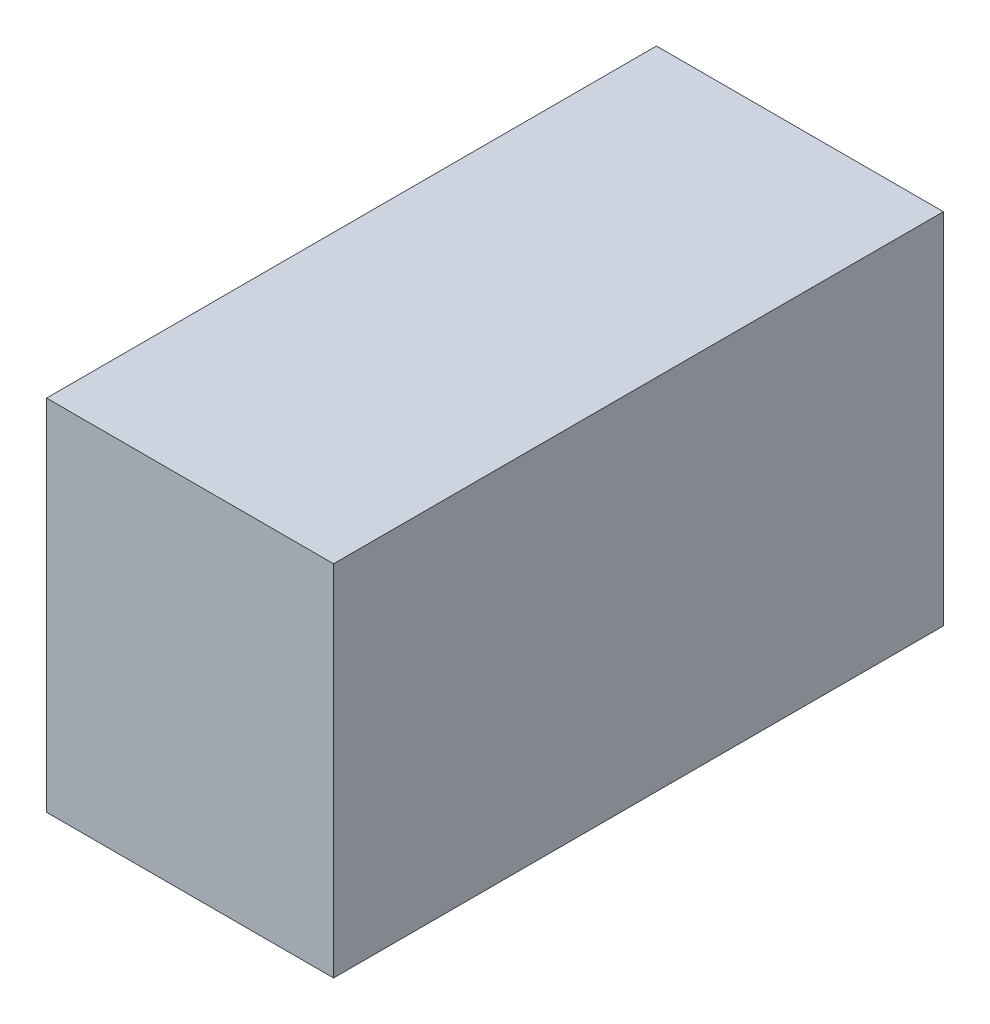
SolidWorks part; units mm, degrees
ref_plane "Front Plane" through (0, 0, 0) normal (0, 0, 1) x (1, 0, 0)
ref_plane "Top Plane" through (0, 0, 0) normal (0, 1, 0) x (1, 0, 0)
ref_plane "Right Plane" through (0, 0, 0) normal (1, 0, 0) x (0, 0, -1)
sketch "Sketch1" plane through (0, 0, 0) normal (0, 0, 1) x (1, 0, 0)
  line L1 (-12.7, 15.875) -> (12.7, 15.875)
  line L2 (-12.7, 15.875) -> (-12.7, -15.875)
  line L3 (-12.7, -15.875) -> (12.7, -15.875)
  line L4 (12.7, 15.875) -> (12.7, -15.875)
  line L5 (-12.7, 15.875) -> (12.7, -15.875) construction
  line L6 (-12.7, -15.875) -> (12.7, 15.875) construction
  point P0 (0, 0)
  dimension "D1" = 25.4
  dimension "D2" = 31.75
extrude "Boss-Extrude1" add sketch "Sketch1" along normal mid plane 53.975
sketch "Sketch2" plane through (0, 0, 0) normal (0, 0, 1) x (1, 0, 0)
  line L0 (12.7, 15.875) -> (-12.7, 15.875) construction
  line L1 (-12.446, -15.621) -> (12.446, -15.621)
  line L2 (-12.446, -15.621) -> (-12.446, 15.621)
  line L3 (-12.446, 15.621) -> (12.446, 15.621)
  line L4 (12.446, -15.621) -> (12.446, 15.621)
  line L5 (-12.446, -15.621) -> (12.446, 15.621) construction
  line L6 (-12.446, 15.621) -> (12.446, -15.621) construction
  line L7 (12.7, -15.875) -> (12.7, 15.875) construction
  point P0 (0, 0)
  dimension "D1" = 0.254
  dimension "D2" = 0.254
extrude "Boss-Extrude2" add sketch "Sketch2" along normal mid plane 53.467 separate body
sketch "Sketch3" plane through (12.446, 0, 0) normal (1, 0, 0) x (0, 0, -1)
  line L0 (-26.7335, 11.7223) -> (-20.3835, 14.0335)
  line L1 (-26.7335, -15.621) -> (-26.7335, 15.621) construction
  line L2 (-20.3835, 14.0335) -> (-20.3835, 15.621)
  line L3 (-26.7335, 15.621) -> (26.7335, 15.621) construction
  line L4 (-20.3835, 15.621) -> (-26.7335, 15.621)
  line L5 (-26.7335, 15.621) -> (-26.7335, 11.7223)
  line L6 (-20.3835, 14.0335) -> (-26.7335, 14.0335) construction
  line L7 (-25.7351, 12.0857) -> (-26.7335, 11.0873) construction
  line L8 (-26.7335, 11.0873) -> (-26.7335, 11.7223) construction
  line L9 (-26.7335, 11.7223) -> (-25.7351, 12.0857) construction
  line L10 (-26.7335, 11.7223) -> (-26.7335, 11.0873) construction
  dimension "D1" = 1.5875
  dimension "D3" = 20
  dimension "D4" = 45
  dimension "D5" = 0.635
extrude "Cut-Extrude1" cut sketch "Sketch3" against normal through all
mirror "Mirror1" about plane through (0, 0, 0) normal (0, 1, 0) of "Cut-Extrude1"
mirror "Mirror2" about plane through (0, 0, 0) normal (0, 0, 1) of "Mirror1", "Cut-Extrude1"
sketch "Sketch4" plane through (0, 15.621, 0) normal (0, 1, 0) x (1, 0, 0)
  line L0 (-12.446, 26.7335) -> (-12.446, 20.3835)
  line L2 (-12.446, -20.3835) -> (-12.446, 20.3835) construction
  line L3 (-12.446, 20.3835) -> (-10.8585, 20.3835)
  line L5 (-10.8585, 20.3835) -> (-8.5473, 26.7335)
  line L8 (-8.5473, 26.7335) -> (-12.446, 26.7335)
  line L9 (-10.8585, 20.3835) -> (-10.8585, 26.7335) construction
  dimension "D3" = 6.35
  dimension "D4" = 1.5875
  dimension "D5" = 20
extrude "Cut-Extrude2" cut sketch "Sketch4" against normal through all and the other way through all
mirror "Mirror3" about plane through (0, 0, 0) normal (1, 0, 0) of "Cut-Extrude2"
mirror "Mirror4" about plane through (0, 0, 0) normal (0, 0, 1) of "Mirror3", "Cut-Extrude2"
chamfer "Chamfer1" [suppressed] distance 2.54 angle 45
sketch "Sketch5" plane through (0, 0, 0) normal (1, 0, 0) x (0, 0, -1)
  line L0 (12.6662, 224.3643) -> (176.6662, 224.3643) construction
sketch "Sketch6" plane through (0, -15.621, 0) normal (0, -1, 0) x (1, 0, 0)
  circle A0 centre (0, 0) radius 9.906 construction
  circle A1 centre (0, 0) radius 9.906 construction
  circle A2 centre (0, 0) radius 5.7544
  dimension "D1" = 11.5087
extrude "Cut-Extrude3" cut sketch "Sketch6" against normal up to surface (12.446 mm away)
sketch "Sketch7" plane through (0, -15.621, 0) normal (0, -1, 0) x (1, 0, 0)
  circle A0 centre (0, 0) radius 9.906 construction
  circle A1 centre (0, 0) radius 9.906 construction
  circle A2 centre (0, 0) radius 7.3419
  dimension "D1" = 14.6837
extrude "Cut-Extrude5" cut sketch "Sketch7" against normal up to surface (6.096 mm away)
sketch "rightGraphics" plane through (12.446, 0, 0) normal (1, 0, 0) x (0, 0, -1)
  line L2 (26.7335, 11.7223) -> (26.7335, -11.7223)
  line L4 (-26.7335, -11.7223) -> (-26.7335, 11.7223)
  line L10 (26.7335, -11.7223) -> (20.3835, -14.0335)
  line L11 (26.7335, -11.7223) -> (20.3835, -14.0335)
  line L12 (20.3835, -14.0335) -> (20.3835, -15.621)
  line L14 (20.3835, -15.621) -> (-20.3835, -15.621)
  line L16 (-20.3835, -15.621) -> (-20.3835, -14.0335)
  line L18 (-20.3835, -14.0335) -> (-26.7335, -11.7223)
  line L19 (-20.3835, -14.0335) -> (-26.7335, -11.7223)
  line L30 (-26.7335, 11.7223) -> (-20.3835, 14.0335)
  line L31 (-26.7335, 11.7223) -> (-20.3835, 14.0335)
  line L32 (-20.3835, 14.0335) -> (-20.3835, 15.621)
  line L34 (-20.3835, 15.621) -> (20.3835, 15.621)
  line L36 (20.3835, 15.621) -> (20.3835, 14.0335)
  line L38 (20.3835, 14.0335) -> (26.7335, 11.7223)
  line L39 (20.3835, 14.0335) -> (26.7335, 11.7223)
  line L41 (26.7335, 11.7223) -> (26.7335, -11.7223)
  line L46 (20.3835, -14.0335) -> (20.3835, -15.621)
  line L47 (20.3835, -15.621) -> (-20.3835, -15.621)
  line L48 (-20.3835, -15.621) -> (-20.3835, -14.0335)
  line L52 (-26.7335, -11.7223) -> (-26.7335, 11.7223)
  line L56 (-20.3835, 14.0335) -> (-20.3835, 15.621)
  line L57 (-20.3835, 15.621) -> (20.3835, 15.621)
  line L58 (20.3835, 15.621) -> (20.3835, 14.0335)
sketch "topGraphics" plane through (0, 15.621, 0) normal (0, 1, 0) x (1, 0, 0)
  line L0 (-8.5473, 26.7335) -> (8.5473, 26.7335)
  line L2 (-8.5473, 26.7335) -> (8.5473, 26.7335)
  line L4 (8.5473, -26.7335) -> (-8.5473, -26.7335)
  line L10 (8.5473, 26.7335) -> (10.8585, 20.3835)
  line L11 (8.5473, 26.7335) -> (10.8585, 20.3835)
  line L12 (10.8585, 20.3835) -> (12.446, 20.3835)
  line L14 (12.446, 20.3835) -> (12.446, -20.3835)
  line L16 (12.446, -20.3835) -> (10.8585, -20.3835)
  line L18 (10.8585, -20.3835) -> (8.5473, -26.7335)
  line L19 (10.8585, -20.3835) -> (8.5473, -26.7335)
  line L30 (-8.5473, -26.7335) -> (-10.8585, -20.3835)
  line L31 (-8.5473, -26.7335) -> (-10.8585, -20.3835)
  line L32 (-10.8585, -20.3835) -> (-12.446, -20.3835)
  line L34 (-12.446, -20.3835) -> (-12.446, 20.3835)
  line L36 (-12.446, 20.3835) -> (-10.8585, 20.3835)
  line L38 (-10.8585, 20.3835) -> (-8.5473, 26.7335)
  line L39 (-10.8585, 20.3835) -> (-8.5473, 26.7335)
  line L42 (8.5473, -26.7335) -> (-8.5473, -26.7335)
  line L46 (10.8585, 20.3835) -> (12.446, 20.3835)
  line L47 (12.446, 20.3835) -> (12.446, -20.3835)
  line L48 (12.446, -20.3835) -> (10.8585, -20.3835)
  line L56 (-10.8585, -20.3835) -> (-12.446, -20.3835)
  line L57 (-12.446, -20.3835) -> (-12.446, 20.3835)
  line L58 (-12.446, 20.3835) -> (-10.8585, 20.3835)
sketch "bottomGraphics" plane through (0, -15.621, 0) normal (0, -1, 0) x (1, 0, 0)
  line L0 (-8.5473, 26.7335) -> (8.5473, 26.7335)
  line L2 (-8.5473, 26.7335) -> (8.5473, 26.7335)
  line L4 (8.5473, -26.7335) -> (-8.5473, -26.7335)
  line L10 (8.5473, 26.7335) -> (10.8585, 20.3835)
  line L11 (8.5473, 26.7335) -> (10.8585, 20.3835)
  line L12 (10.8585, 20.3835) -> (12.446, 20.3835)
  line L14 (12.446, 20.3835) -> (12.446, -20.3835)
  line L16 (12.446, -20.3835) -> (10.8585, -20.3835)
  line L18 (10.8585, -20.3835) -> (8.5473, -26.7335)
  line L19 (10.8585, -20.3835) -> (8.5473, -26.7335)
  line L30 (-8.5473, -26.7335) -> (-10.8585, -20.3835)
  line L31 (-8.5473, -26.7335) -> (-10.8585, -20.3835)
  line L32 (-10.8585, -20.3835) -> (-12.446, -20.3835)
  line L34 (-12.446, -20.3835) -> (-12.446, 20.3835)
  line L36 (-12.446, 20.3835) -> (-10.8585, 20.3835)
  line L38 (-10.8585, 20.3835) -> (-8.5473, 26.7335)
  line L39 (-10.8585, 20.3835) -> (-8.5473, 26.7335)
  line L42 (8.5473, -26.7335) -> (-8.5473, -26.7335)
  line L46 (10.8585, 20.3835) -> (12.446, 20.3835)
  line L47 (12.446, 20.3835) -> (12.446, -20.3835)
  line L48 (12.446, -20.3835) -> (10.8585, -20.3835)
  line L56 (-10.8585, -20.3835) -> (-12.446, -20.3835)
  line L57 (-12.446, -20.3835) -> (-12.446, 20.3835)
  line L58 (-12.446, 20.3835) -> (-10.8585, 20.3835)
  circle A0 centre (0, 0) radius 7.3419 construction
  circle A1 centre (0, 0) radius 5.7544 construction
  circle A2 centre (0, 0) radius 7.3419
  circle A3 centre (0, 0) radius 5.7544
sketch "frontGraphics" [suppressed] plane through (0, 0, 26.7335) normal (0, 0, 1) x (1, 0, 0)
  line L2 (-12.446, -15.621) -> (-12.446, 15.621)
  line L3 (-12.446, -15.621) -> (-12.446, 15.621)
  line L6 (-12.446, 15.621) -> (12.446, 15.621)
  line L7 (-12.446, 15.621) -> (12.446, 15.621)
  line L10 (12.446, 15.621) -> (12.446, -15.621)
  line L11 (12.446, 15.621) -> (12.446, -15.621)
  line L14 (12.446, -15.621) -> (-12.446, -15.621)
  line L15 (12.446, -15.621) -> (-12.446, -15.621)
  line L16 (-8.5473, -11.0873) -> (8.5473, -11.0873) construction
  line L17 (-8.5473, -11.0873) -> (-8.5473, 11.0873) construction
  line L18 (8.5473, 11.0873) -> (-8.5473, 11.0873) construction
  line L19 (8.5473, -11.0873) -> (8.5473, 11.0873) construction
  line L20 (-8.5473, -11.0873) -> (8.5473, -11.0873)
  line L21 (-8.5473, -11.0873) -> (-8.5473, 11.0873)
  line L22 (8.5473, 11.0873) -> (-8.5473, 11.0873)
  line L23 (8.5473, -11.0873) -> (8.5473, 11.0873)
sketch "Sketch9" plane through (0, 15.621, 0) normal (0, 1, 0) x (1, 0, 0)
  line L0 (-11.8694, 19.8069) -> (-11.8694, -19.8069)
  line L1 (-11.8694, -19.8069) -> (11.8694, -19.8069)
  line L2 (11.8694, -19.8069) -> (11.8694, 19.8069)
  line L3 (11.8694, 19.8069) -> (-11.8694, 19.8069)
  line L4 (12.446, 20.3835) -> (-12.446, 20.3835)
  line L5 (-12.446, 20.3835) -> (-12.446, -20.3835)
  line L6 (-12.446, -20.3835) -> (12.446, -20.3835)
  line L7 (12.446, -20.3835) -> (12.446, 20.3835)
  line L8 (12.446, 20.3835) -> (-12.446, 20.3835) construction
  line L9 (-12.446, 20.3835) -> (-12.446, -20.3835) construction
  line L10 (-12.446, -20.3835) -> (12.446, -20.3835) construction
  line L11 (12.446, -20.3835) -> (12.446, 20.3835) construction
  line L12 (-3.8718, 3.8718) -> (-11.6154, 3.8718) construction
  line L13 (-3.8718, -3.8718) -> (3.8718, -3.8718) construction
  line L14 (-3.8718, -3.8718) -> (-3.8718, 3.8718) construction
  line L15 (-3.8718, 3.8718) -> (3.8718, 3.8718) construction
  line L16 (3.8718, -3.8718) -> (3.8718, 3.8718) construction
  line L17 (-3.8718, -3.8718) -> (3.8718, 3.8718) construction
  line L18 (-3.8718, 3.8718) -> (3.8718, -3.8718) construction
  line L19 (3.8718, 3.8718) -> (11.6154, 3.8718) construction
  line L20 (-11.6154, 19.8069) -> (-11.6154, -19.8069)
  line L21 (11.6154, -19.8069) -> (11.6154, 19.8069)
  line L22 (-3.7448, -3.7448) -> (3.7448, -3.7448) construction
  line L23 (3.7448, -3.7448) -> (3.7448, 3.7448) construction
  line L24 (-3.7448, 3.7448) -> (3.7448, 3.7448) construction
  line L25 (-3.7448, -3.7448) -> (-3.7448, 3.7448) construction
  line L26 (0, 0) -> (-11.6154, 0) construction
  line L27 (0, 0) -> (0, -19.8069) construction
  line L28 (-11.8694, -19.5529) -> (11.8694, -19.5529)
  line L29 (11.8694, 19.5529) -> (-11.8694, 19.5529)
  circle A0 centre (0, 0) radius 3.7448
  circle A1 centre (0, 0) radius 3.2368
  circle A2 centre (3.8735, 0) radius 3.2368
  circle A3 centre (3.8735, 0) radius 3.7448
  circle A4 centre (7.747, 0) radius 3.2368
  circle A5 centre (7.747, 0) radius 3.7448
  arc A6 (11.6154, 3.2368) -> (11.6154, -3.2368) centre (11.6205, 0) ccw
  arc A7 (11.6154, 3.7448) -> (11.6154, -3.7448) centre (11.6205, 0) ccw
  circle A8 centre (3.8735, 3.8862) radius 3.2368
  circle A9 centre (3.8735, 3.8862) radius 3.7448
  circle A10 centre (7.747, 3.8862) radius 3.2368
  circle A11 centre (7.747, 3.8862) radius 3.7448
  arc A12 (11.6154, 7.123) -> (11.6154, 0.6494) centre (11.6205, 3.8862) ccw
  arc A13 (11.6154, 7.631) -> (11.6154, 0.1414) centre (11.6205, 3.8862) ccw
  circle A14 centre (3.8735, 7.7724) radius 3.2368
  circle A15 centre (3.8735, 7.7724) radius 3.7448
  circle A16 centre (7.747, 7.7724) radius 3.2368
  circle A17 centre (7.747, 7.7724) radius 3.7448
  arc A18 (11.6154, 11.0092) -> (11.6154, 4.5356) centre (11.6205, 7.7724) ccw
  arc A19 (11.6154, 11.5172) -> (11.6154, 4.0276) centre (11.6205, 7.7724) ccw
  circle A20 centre (3.8735, 11.6586) radius 3.2368
  circle A21 centre (3.8735, 11.6586) radius 3.7448
  circle A22 centre (7.747, 11.6586) radius 3.2368
  circle A23 centre (7.747, 11.6586) radius 3.7448
  arc A24 (11.6154, 14.8954) -> (11.6154, 8.4218) centre (11.6205, 11.6586) ccw
  arc A25 (11.6154, 15.4034) -> (11.6154, 7.9138) centre (11.6205, 11.6586) ccw
  circle A26 centre (3.8735, 15.5448) radius 3.2368
  circle A27 centre (3.8735, 15.5448) radius 3.7448
  circle A28 centre (7.747, 15.5448) radius 3.2368
  circle A29 centre (7.747, 15.5448) radius 3.7448
  arc A30 (11.6154, 18.7816) -> (11.6154, 12.308) centre (11.6205, 15.5448) ccw
  arc A31 (11.6154, 19.2896) -> (11.6154, 11.8) centre (11.6205, 15.5448) ccw
  arc A32 (0.639, 19.5529) -> (7.108, 19.5529) centre (3.8735, 19.431) ccw
  arc A33 (0.1307, 19.5529) -> (7.6163, 19.5529) centre (3.8735, 19.431) ccw
  arc A34 (4.5125, 19.5529) -> (10.9815, 19.5529) centre (7.747, 19.431) ccw
  arc A35 (4.0042, 19.5529) -> (11.4898, 19.5529) centre (7.747, 19.431) ccw
  circle A38 centre (0, 3.8862) radius 3.2368
  circle A39 centre (0, 3.8862) radius 3.7448
  circle A40 centre (0, 7.7724) radius 3.2368
  circle A41 centre (0, 7.7724) radius 3.7448
  circle A42 centre (0, 11.6586) radius 3.2368
  circle A43 centre (0, 11.6586) radius 3.7448
  circle A44 centre (0, 15.5448) radius 3.2368
  circle A45 centre (0, 15.5448) radius 3.7448
  arc A46 (-3.2345, 19.5529) -> (3.2345, 19.5529) centre (0, 19.431) ccw
  arc A47 (-3.7428, 19.5529) -> (3.7428, 19.5529) centre (0, 19.431) ccw
  circle A48 centre (-3.8735, 0) radius 3.2368
  circle A49 centre (-3.8735, 0) radius 3.7448
  circle A52 centre (-7.747, 0) radius 3.2368
  circle A53 centre (-7.747, 0) radius 3.7448
  circle A58 centre (-7.747, 3.8862) radius 3.2368
  circle A59 centre (-7.747, 3.8862) radius 3.7448
  circle A60 centre (-7.747, 7.7724) radius 3.2368
  circle A61 centre (-7.747, 7.7724) radius 3.7448
  circle A62 centre (-7.747, 11.6586) radius 3.7448
  circle A63 centre (-7.747, 11.6586) radius 3.2368
  circle A68 centre (-7.747, 15.5448) radius 3.2368
  circle A69 centre (-7.747, 15.5448) radius 3.7448
  circle A76 centre (-3.8735, 15.5448) radius 3.7448
  circle A77 centre (-3.8735, 15.5448) radius 3.2368
  circle A78 centre (-3.8735, 11.6586) radius 3.2368
  circle A79 centre (-3.8735, 11.6586) radius 3.7448
  circle A80 centre (-3.8735, 7.7724) radius 3.7448
  circle A81 centre (-3.8735, 7.7724) radius 3.2368
  circle A82 centre (-3.8735, 3.8862) radius 3.2368
  circle A83 centre (-3.8735, 3.8862) radius 3.7448
  circle A84 centre (7.747, -7.7724) radius 3.2368
  circle A85 centre (7.747, -7.7724) radius 3.7448
  circle A86 centre (7.747, -11.6586) radius 3.2368
  circle A87 centre (7.747, -11.6586) radius 3.7448
  circle A88 centre (7.747, -15.5448) radius 3.2368
  circle A89 centre (7.747, -15.5448) radius 3.7448
  circle A90 centre (3.8735, -15.5448) radius 3.2368
  circle A91 centre (3.8735, -15.5448) radius 3.7448
  circle A92 centre (3.8735, -7.7724) radius 3.2368
  circle A93 centre (3.8735, -7.7724) radius 3.7448
  circle A94 centre (3.8735, -11.6586) radius 3.2368
  circle A95 centre (3.8735, -11.6586) radius 3.7448
  circle A96 centre (0, -7.7724) radius 3.7448
  circle A97 centre (0, -7.7724) radius 3.2368
  circle A98 centre (0, -11.6586) radius 3.2368
  circle A99 centre (0, -15.5448) radius 3.2368
  circle A100 centre (0, -15.5448) radius 3.7448
  circle A101 centre (0, -11.6586) radius 3.7448
  circle A102 centre (-3.8735, -7.7724) radius 3.2368
  circle A103 centre (-3.8735, -7.7724) radius 3.7448
  circle A104 centre (-3.8735, -11.6586) radius 3.2368
  circle A105 centre (-3.8735, -11.6586) radius 3.7448
  circle A106 centre (-3.8735, -15.5448) radius 3.2368
  circle A107 centre (-3.8735, -15.5448) radius 3.7448
  circle A108 centre (-7.747, -15.5448) radius 3.2368
  circle A109 centre (-7.747, -15.5448) radius 3.7448
  circle A110 centre (-7.747, -11.6586) radius 3.2368
  circle A111 centre (-7.747, -7.7724) radius 3.2368
  circle A112 centre (-7.747, -11.6586) radius 3.7448
  circle A113 centre (-7.747, -7.7724) radius 3.7448
  arc A120 (-8.386, -19.5529) -> (-11.6154, -16.1942) centre (-11.6205, -19.431) ccw
  arc A121 (-7.8777, -19.5529) -> (-11.6154, -15.6862) centre (-11.6205, -19.431) ccw
  arc A122 (-4.5125, -19.5529) -> (-10.9815, -19.5529) centre (-7.747, -19.431) ccw
  arc A123 (-4.0042, -19.5529) -> (-11.4898, -19.5529) centre (-7.747, -19.431) ccw
  arc A124 (-0.639, -19.5529) -> (-7.108, -19.5529) centre (-3.8735, -19.431) ccw
  arc A125 (-0.1307, -19.5529) -> (-7.6163, -19.5529) centre (-3.8735, -19.431) ccw
  arc A135 (11.6154, -19.2896) -> (11.6154, -11.8) centre (11.6205, -15.5448) cw
  circle A142 centre (7.747, -3.8862) radius 3.7448
  circle A143 centre (7.747, -3.8862) radius 3.2368
  circle A144 centre (3.8735, -3.8862) radius 3.7448
  circle A145 centre (3.8735, -3.8862) radius 3.2368
  circle A146 centre (0, -3.8862) radius 3.2368
  circle A147 centre (0, -3.8862) radius 3.7448
  circle A148 centre (-3.8735, -3.8862) radius 3.2368
  circle A149 centre (-3.8735, -3.8862) radius 3.7448
  circle A150 centre (-7.747, -3.8862) radius 3.2368
  circle A151 centre (-7.747, -3.8862) radius 3.7448
  arc A154 (8.386, -19.5529) -> (11.6154, -16.1942) centre (11.6205, -19.431) cw
  arc A155 (7.8777, -19.5529) -> (11.6154, -15.6862) centre (11.6205, -19.431) cw
  arc A156 (4.5125, -19.5529) -> (10.9815, -19.5529) centre (7.747, -19.431) cw
  arc A157 (4.0042, -19.5529) -> (11.4898, -19.5529) centre (7.747, -19.431) cw
  arc A160 (-4.5125, 19.5529) -> (-10.9815, 19.5529) centre (-7.747, 19.431) cw
  arc A161 (0.639, -19.5529) -> (7.108, -19.5529) centre (3.8735, -19.431) cw
  arc A162 (0.1307, -19.5529) -> (7.6163, -19.5529) centre (3.8735, -19.431) cw
  arc A163 (-3.2345, -19.5529) -> (3.2345, -19.5529) centre (0, -19.431) cw
  arc A164 (-3.7428, -19.5529) -> (3.7428, -19.5529) centre (0, -19.431) cw
  arc A165 (-4.0042, 19.5529) -> (-11.4898, 19.5529) centre (-7.747, 19.431) cw
  arc A166 (-0.639, 19.5529) -> (-7.108, 19.5529) centre (-3.8735, 19.431) cw
  arc A167 (-0.1307, 19.5529) -> (-7.6163, 19.5529) centre (-3.8735, 19.431) cw
  arc A170 (-11.6154, -18.7816) -> (-11.6154, -12.308) centre (-11.6205, -15.5448) ccw
  arc A171 (-11.6154, -19.2896) -> (-11.6154, -11.8) centre (-11.6205, -15.5448) ccw
  arc A172 (7.8777, 19.5529) -> (11.6154, 15.6862) centre (11.6205, 19.431) ccw
  arc A173 (8.386, 19.5529) -> (11.6154, 16.1942) centre (11.6205, 19.431) ccw
  arc A174 (11.6154, -7.123) -> (11.6154, -0.6494) centre (11.6205, -3.8862) cw
  arc A175 (11.6154, -7.631) -> (11.6154, -0.1414) centre (11.6205, -3.8862) cw
  arc A176 (-11.6154, -11.0092) -> (-11.6154, -4.5356) centre (-11.6205, -7.7724) ccw
  arc A177 (11.6154, -14.8954) -> (11.6154, -8.4218) centre (11.6205, -11.6586) cw
  arc A178 (11.6154, -15.4034) -> (11.6154, -7.9138) centre (11.6205, -11.6586) cw
  arc A179 (-11.6154, -11.5172) -> (-11.6154, -4.0276) centre (-11.6205, -7.7724) ccw
  arc A180 (11.6154, -18.7816) -> (11.6154, -12.308) centre (11.6205, -15.5448) cw
  arc A181 (11.6154, -11.0092) -> (11.6154, -4.5356) centre (11.6205, -7.7724) cw
  arc A182 (11.6154, -11.5172) -> (11.6154, -4.0276) centre (11.6205, -7.7724) cw
  arc A183 (10.1416, 22.3102) -> (9.6837, 22.0244) centre (11.6205, 19.431) ccw
  arc A184 (9.6837, 22.6361) -> (9.2259, 22.3102) centre (11.6205, 19.431) ccw
  arc A187 (-11.6154, -14.8954) -> (-11.6154, -8.4218) centre (-11.6205, -11.6586) ccw
  arc A188 (-11.6154, -15.4034) -> (-11.6154, -7.9138) centre (-11.6205, -11.6586) ccw
  arc A195 (-11.6154, -7.123) -> (-11.6154, -0.6494) centre (-11.6205, -3.8862) ccw
  arc A196 (-11.6154, 3.2368) -> (-11.6154, -3.2368) centre (-11.6205, 0) cw
  arc A197 (-11.6154, 3.7448) -> (-11.6154, -3.7448) centre (-11.6205, 0) cw
  arc A200 (-11.6154, 7.123) -> (-11.6154, 0.6494) centre (-11.6205, 3.8862) cw
  arc A201 (-11.6154, -7.631) -> (-11.6154, -0.1414) centre (-11.6205, -3.8862) ccw
  arc A202 (-11.6154, 7.631) -> (-11.6154, 0.1414) centre (-11.6205, 3.8862) cw
  arc A205 (-11.6154, 11.0092) -> (-11.6154, 4.5356) centre (-11.6205, 7.7724) cw
  arc A206 (-11.6154, 11.5172) -> (-11.6154, 4.0276) centre (-11.6205, 7.7724) cw
  arc A209 (-11.6154, 14.8954) -> (-11.6154, 8.4218) centre (-11.6205, 11.6586) cw
  arc A210 (-11.6154, 15.4034) -> (-11.6154, 7.9138) centre (-11.6205, 11.6586) cw
  arc A213 (-11.6154, 18.7816) -> (-11.6154, 12.308) centre (-11.6205, 15.5448) cw
  arc A214 (-11.6154, 19.2896) -> (-11.6154, 11.8) centre (-11.6205, 15.5448) cw
  arc A219 (-7.8777, 19.5529) -> (-11.6154, 15.6862) centre (-11.6205, 19.431) cw
  arc A220 (-8.386, 19.5529) -> (-11.6154, 16.1942) centre (-11.6205, 19.431) cw
  point P8 (0, 0)
  dimension "D7" = 0.254
  dimension "D10" = 3.8735
  dimension "D1" = 0
  dimension "D2" = 0.5766
  dimension "D3" = 0.254
  dimension "D4" = 0.254
  dimension "D5" = 0.127
  dimension "D6" = 0.508
  dimension "D8" = 4
  dimension "D9" = 6
equation "\"cleanup\"= 0.01"
equation "\"D1@Sketch2\"= \"cleanup\""
equation "\"D2@Sketch2\"=\"cleanup\""
equation "\"step\"=0.0625"
equation "\"D1@Sketch3\"=\"step\""
equation "\"depth\"=0.25"
equation "\"D2@Sketch3\"=\"depth\""
equation "\"D3@Sketch4\"=\"depth\""
equation "\"D4@Sketch4\"=\"step\""
equation "\"larger_hole_diamter\"= 0.4531"
equation "\"D1@Sketch6\"=\"larger_hole_diamter\""
equation "\"large_thread_diamter\"= 0.5781"
equation "\"D1@Sketch7\"=\"large_thread_diamter\""
